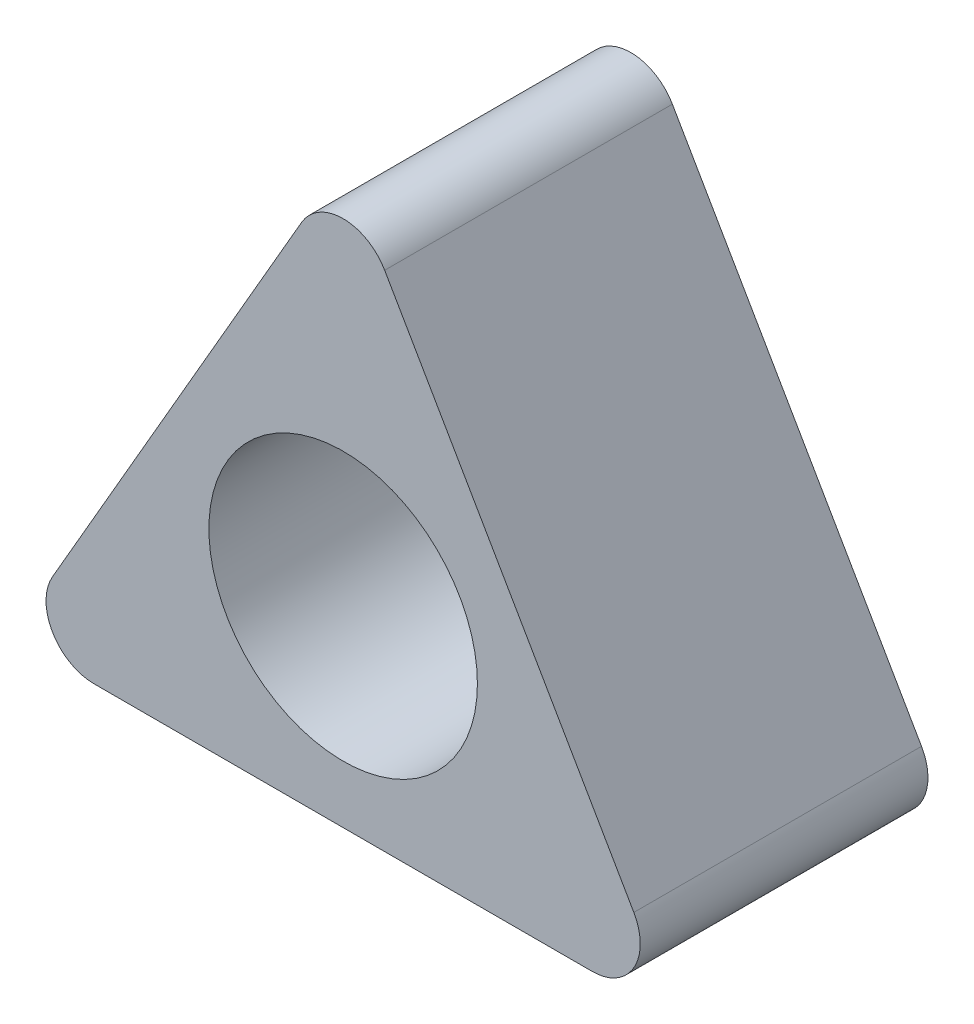
SolidWorks part; units mm, degrees
ref_plane "Front Plane" through (0, 0, 0) normal (0, 0, 1) x (1, 0, 0)
ref_plane "Top Plane" through (0, 0, 0) normal (0, 1, 0) x (1, 0, 0)
ref_plane "Right Plane" through (0, 0, 0) normal (1, 0, 0) x (0, 0, -1)
sketch "Sketch1" plane through (0, 0, 0) normal (0, 0, 1) x (1, 0, 0)
  line L0 (0, 40) -> (34.641, -20)
  line L1 (34.641, -20) -> (-34.641, -20)
  line L2 (-34.641, -20) -> (0, 40)
  line L3 (0, 0) -> (-17.3205, 10) construction
  point P3 (0, -20)
  dimension "D1" = 20
extrude "Boss-Extrude1" add sketch "Sketch1" along normal blind 30
fillet "Fillet1" radius 5 3 edges at (34.641, -20, 15) (-34.641, -20, 15) (0, 40, 15)
sketch "Sketch2" plane through (0, 0, 30) normal (0, 0, 1) x (1, 0, 0)
  circle A0 centre (0, 0) radius 14
  dimension "D1" = 28
extrude "Cut-Extrude1" cut sketch "Sketch2" against normal through all
